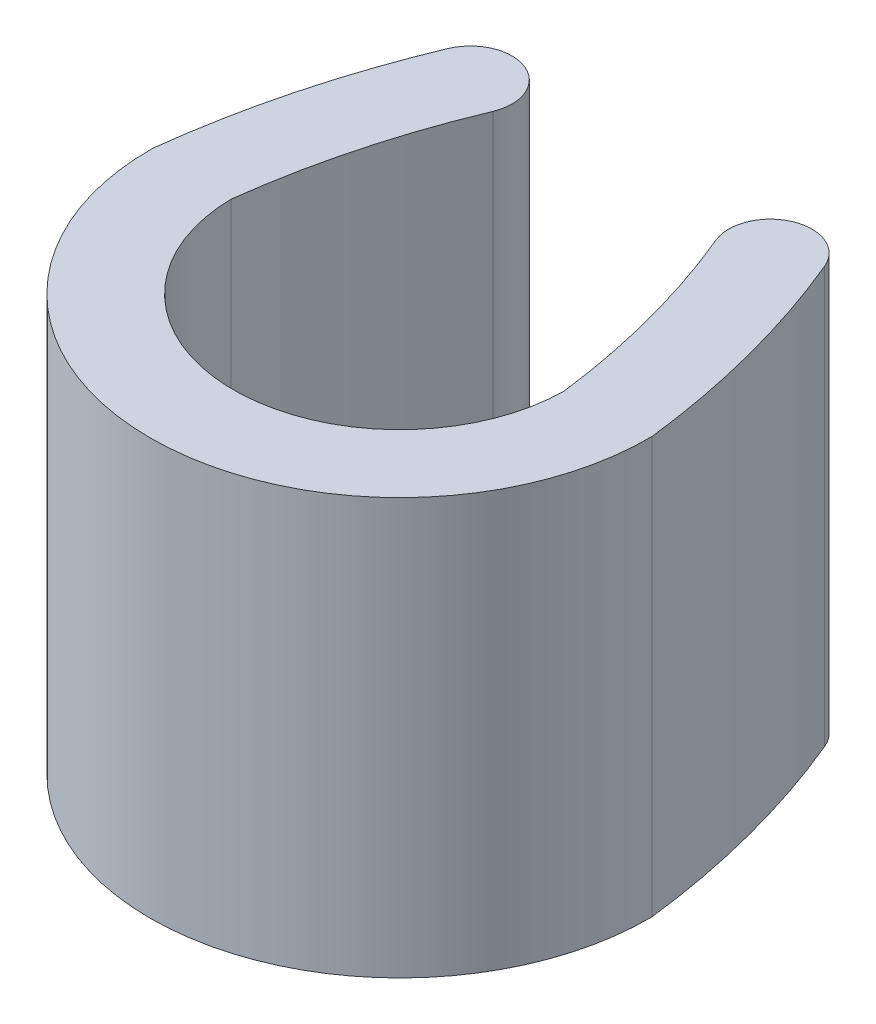
SolidWorks part; units mm, degrees
ref_plane "Front Plane" through (0, 0, 0) normal (0, 0, 1) x (1, 0, 0)
ref_plane "Top Plane" through (0, 0, 0) normal (0, 1, 0) x (1, 0, 0)
ref_plane "Right Plane" through (0, 0, 0) normal (1, 0, 0) x (0, 0, -1)
sketch "Sketch1" plane through (0, 0, 0) normal (0, 1, 0) x (1, 0, 0)
  line L0 (0, 2.5) -> (0, -5.1281) construction
  line L1 (-4.9468, 0) -> (5.0173, 0) construction
  arc A0 (-2.5, 0) -> (2.5, 0) centre (0, 0) ccw
  arc A1 (-2.5, 0) -> (-1.802, 2.6505) centre (7.428, -1.1974) cw
  arc A2 (2.5, 0) -> (1.802, 2.6505) centre (-7.428, -1.1974) ccw
  arc A3 (1.9998, -0.0288) -> (1.3405, 2.4581) centre (-7.428, -1.1974) ccw
  arc A4 (-1.9998, -0.0288) -> (1.9998, -0.0288) centre (0, 0) ccw
  arc A5 (-1.9998, -0.0288) -> (-1.3405, 2.4581) centre (7.428, -1.1974) cw
  arc A6 (2.9998, 0.031) -> (2.2635, 2.8429) centre (-7.428, -1.1974) ccw
  arc A7 (-2.9998, 0.031) -> (2.9998, 0.031) centre (0, 0) ccw
  arc A8 (-2.9998, 0.031) -> (-2.2635, 2.8429) centre (7.428, -1.1974) cw
  arc A9 (-2.2635, 2.8429) -> (-1.3405, 2.4581) centre (-1.802, 2.6505) cw
  arc A10 (2.2635, 2.8429) -> (1.3585, 2.4196) centre (1.802, 2.6505) ccw
  point P28 (0, 0)
  point P29 (2, 2.6089)
  point P30 (1.802, 2.6505)
  dimension "D1" = 5
  dimension "D2" = 10
  dimension "D3" = 0.5
  dimension "D4" = 0.5
extrude "Boss-Extrude1" add sketch "Sketch1" along normal blind 5
